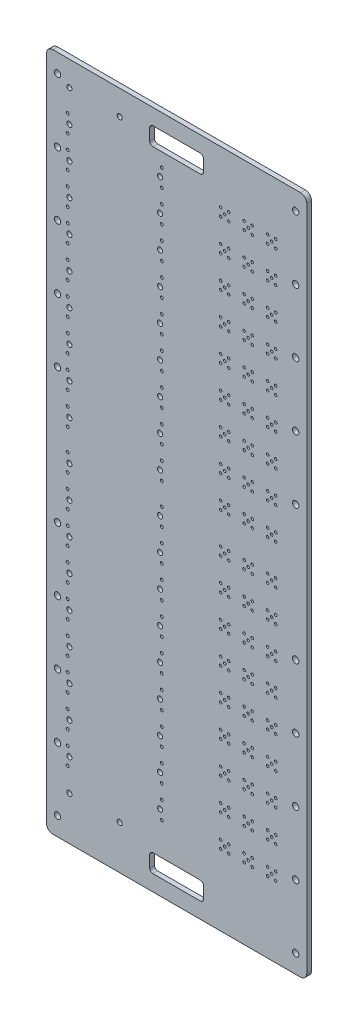
SolidWorks part; units mm, degrees
ref_plane "Front Plane" through (0, 0, 0) normal (0, 0, 1) x (1, 0, 0)
ref_plane "Top Plane" through (0, 0, 0) normal (0, 1, 0) x (1, 0, 0)
ref_plane "Right Plane" through (0, 0, 0) normal (1, 0, 0) x (0, 0, -1)
ref_plane "Plane1" through (0, 0, 0) normal (0, 0, -1) x (-1, 0, 0)
sketch "Sketch1" plane through (0, 0, 0) normal (0, 0, -1) x (-1, 0, 0)
  line L0 (7.475, 96.3) -> (-7.475, 96.3)
  line L1 (-8.475, 97.3) -> (-8.475, 101)
  line L2 (-7.475, 102) -> (7.475, 102)
  line L3 (8.475, 101) -> (8.475, 97.3)
  line L4 (39, 107) -> (-39, 107)
  line L5 (-41, 105) -> (-41, -105)
  line L6 (-39, -107) -> (39, -107)
  line L7 (41, -105) -> (41, 105)
  line L8 (-8.475, -101) -> (-8.475, -97.3)
  line L9 (-7.475, -96.3) -> (7.475, -96.3)
  line L10 (8.475, -97.3) -> (8.475, -101)
  line L11 (7.475, -102) -> (-7.475, -102)
  line L12 (-37.5, 101.2) -> (-37.5, 81.2) construction
  line L13 (-37.5, 81.2) -> (-37.5, 61.2) construction
  line L14 (-37.5, 61.2) -> (-37.5, 41.2) construction
  line L15 (-37.5, 41.2) -> (-37.5, 21.2) construction
  line L16 (37.5, 101.2) -> (37.5, 81.2) construction
  line L17 (37.5, 81.2) -> (37.5, 61.2) construction
  line L18 (37.5, 61.2) -> (37.5, 41.2) construction
  line L19 (37.5, 41.2) -> (37.5, 21.2) construction
  line L20 (37.5, -21.2) -> (37.5, -41.2) construction
  line L21 (37.5, -41.2) -> (37.5, -61.2) construction
  line L22 (37.5, -61.2) -> (37.5, -81.2) construction
  line L23 (37.5, -81.2) -> (37.5, -101.2) construction
  line L24 (-37.5, -101.2) -> (-37.5, -81.2) construction
  line L25 (-37.5, -81.2) -> (-37.5, -61.2) construction
  line L26 (-37.5, -61.2) -> (-37.5, -41.2) construction
  line L27 (-37.5, -41.2) -> (-37.5, -21.2) construction
  line L28 (33.775, 89.25) -> (5.225, 89.25) construction
  line L29 (-13.87, 87.8811) -> (-16.41, 90.4212) construction
  line L30 (-13.87, 90.4212) -> (-16.41, 87.8812) construction
  line L31 (-13.87, -4.6189) -> (-16.41, -2.0788) construction
  line L32 (-13.87, -2.0788) -> (-16.41, -4.6188) construction
  arc A0 (8.475, 97.3) -> (7.475, 96.3) centre (7.475, 97.3) cw
  arc A1 (-7.475, 96.3) -> (-8.475, 97.3) centre (-7.475, 97.3) cw
  arc A2 (-8.475, 101) -> (-7.475, 102) centre (-7.475, 101) cw
  arc A3 (7.475, 102) -> (8.475, 101) centre (7.475, 101) cw
  circle A4 centre (5.225, -3.25) radius 0.8
  circle A5 centre (34.325, -0.5) radius 0.45
  circle A6 centre (-37.5, 101.2) radius 1
  circle A7 centre (34.325, -6) radius 0.45
  circle A8 centre (34.325, 46.5) radius 0.45
  circle A9 centre (4.675, -6) radius 0.45
  circle A10 centre (5.225, 79.25) radius 0.8
  circle A11 centre (34.325, 82) radius 0.45
  circle A12 centre (33.775, 19.25) radius 0.8
  circle A13 centre (33.775, -3.25) radius 0.8
  circle A14 centre (34.325, 26.5) radius 0.45
  circle A15 centre (4.675, -0.5) radius 0.45
  circle A16 centre (5.225, -13.25) radius 0.8
  circle A17 centre (5.225, 29.25) radius 0.8
  circle A18 centre (34.325, -10.5) radius 0.45
  circle A19 centre (34.325, 36.5) radius 0.45
  circle A20 centre (4.675, 22) radius 0.45
  circle A21 centre (34.325, -16) radius 0.45
  circle A22 centre (5.225, 19.25) radius 0.8
  circle A23 centre (4.675, -16) radius 0.45
  circle A24 centre (33.775, -13.25) radius 0.8
  circle A25 centre (34.325, 76.5) radius 0.45
  circle A26 centre (5.225, 89.25) radius 0.8
  circle A27 centre (4.675, -10.5) radius 0.45
  circle A28 centre (5.225, -23.25) radius 0.8
  circle A29 centre (34.325, -20.5) radius 0.45
  circle A30 centre (4.675, 76.5) radius 0.45
  circle A31 centre (33.775, 79.25) radius 0.8
  circle A32 centre (34.325, 32) radius 0.45
  circle A33 centre (34.325, -26) radius 0.45
  circle A34 centre (4.675, 46.5) radius 0.45
  circle A35 centre (4.675, 26.5) radius 0.45
  circle A36 centre (4.675, -26) radius 0.45
  circle A37 centre (33.775, -23.25) radius 0.8
  circle A38 centre (4.675, -20.5) radius 0.45
  circle A39 centre (5.225, -33.25) radius 0.8
  circle A40 centre (34.325, -30.5) radius 0.45
  circle A41 centre (34.325, -36) radius 0.45
  circle A42 centre (34.325, 92) radius 0.45
  circle A43 centre (33.775, -93.25) radius 0.8
  circle A44 centre (4.675, 32) radius 0.45
  circle A45 centre (4.675, 16.5) radius 0.45
  circle A46 centre (4.675, -36) radius 0.45
  circle A47 centre (4.675, 82) radius 0.45
  circle A48 centre (5.225, 69.25) radius 0.8
  circle A49 centre (34.325, 16.5) radius 0.45
  circle A50 centre (33.775, -33.25) radius 0.8
  circle A51 centre (4.675, -30.5) radius 0.45
  circle A52 centre (4.675, 36.5) radius 0.45
  circle A53 centre (5.225, -43.25) radius 0.8
  circle A54 centre (34.325, 86.5) radius 0.45
  circle A55 centre (33.775, 29.25) radius 0.8
  circle A56 centre (34.325, -40.5) radius 0.45
  circle A57 centre (34.325, -46) radius 0.45
  circle A58 centre (4.675, -46) radius 0.45
  circle A59 centre (33.775, 39.25) radius 0.8
  circle A60 centre (34.325, 72) radius 0.45
  circle A61 centre (34.325, 12) radius 0.45
  arc A62 (-39, 107) -> (-41, 105) centre (-39, 105) ccw
  arc A63 (-41, -105) -> (-39, -107) centre (-39, -105) ccw
  arc A64 (39, -107) -> (41, -105) centre (39, -105) ccw
  arc A65 (41, 105) -> (39, 107) centre (39, 105) ccw
  circle A66 centre (33.775, -43.25) radius 0.8
  circle A67 centre (4.675, -40.5) radius 0.45
  circle A68 centre (34.325, 66.5) radius 0.45
  circle A69 centre (5.225, -53.25) radius 0.8
  circle A70 centre (33.775, 9.25) radius 0.8
  circle A71 centre (34.325, -50.5) radius 0.45
  circle A72 centre (34.325, -56) radius 0.45
  circle A73 centre (4.675, -56) radius 0.45
  circle A74 centre (33.775, -53.25) radius 0.8
  circle A75 centre (4.675, 66.5) radius 0.45
  circle A76 centre (4.675, -50.5) radius 0.45
  circle A77 centre (33.775, 99.25) radius 0.8
  circle A78 centre (5.225, -63.25) radius 0.8
  circle A79 centre (33.775, 69.25) radius 0.8
  circle A80 centre (-37.5, 21.2) radius 1
  circle A81 centre (4.675, 72) radius 0.45
  circle A82 centre (34.325, -60.5) radius 0.45
  circle A83 centre (5.225, 59.25) radius 0.8
  circle A84 centre (4.675, 86.5) radius 0.45
  circle A85 centre (34.325, -66) radius 0.45
  circle A86 centre (4.675, 6.5) radius 0.45
  circle A87 centre (34.325, 62) radius 0.45
  circle A88 centre (4.675, -66) radius 0.45
  circle A89 centre (33.775, -63.25) radius 0.8
  circle A90 centre (4.675, 42) radius 0.45
  circle A91 centre (4.675, -60.5) radius 0.45
  circle A92 centre (34.325, 56.5) radius 0.45
  circle A93 centre (4.675, 56.5) radius 0.45
  circle A94 centre (5.225, -73.25) radius 0.8
  circle A95 centre (33.775, 89.25) radius 0.8
  circle A96 centre (17.925, -93.25) radius 0.8
  circle A97 centre (34.325, 22) radius 0.45
  circle A98 centre (33.775, 59.25) radius 0.8
  circle A99 centre (17.925, 99.25) radius 0.8
  circle A100 centre (4.675, 12) radius 0.45
  circle A101 centre (34.325, -70.5) radius 0.45
  circle A102 centre (4.675, 62) radius 0.45
  circle A103 centre (34.325, -76) radius 0.45
  circle A104 centre (4.675, -76) radius 0.45
  circle A105 centre (5.225, 39.25) radius 0.8
  circle A106 centre (33.775, -73.25) radius 0.8
  circle A107 centre (4.675, -70.5) radius 0.45
  circle A108 centre (-21.27, -12.0789) radius 0.4
  circle A109 centre (-23.81, -12.0789) radius 0.4
  circle A110 centre (-23.81, -14.6189) radius 0.4
  circle A111 centre (-22.54, -13.3489) radius 0.4
  circle A112 centre (-21.27, -14.6189) radius 0.4
  circle A113 centre (37.5, -21.2) radius 1
  circle A114 centre (-28.67, -12.0789) radius 0.4
  circle A115 centre (-31.21, -12.0789) radius 0.4
  circle A116 centre (-31.21, -14.6189) radius 0.4
  circle A117 centre (-29.94, -13.3489) radius 0.4
  circle A118 centre (-28.67, -14.6189) radius 0.4
  circle A119 centre (-13.87, -12.0788) radius 0.4
  circle A120 centre (-16.41, -12.0788) radius 0.4
  circle A121 centre (-16.41, -14.6188) radius 0.4
  circle A122 centre (-15.14, -13.3488) radius 0.4
  circle A123 centre (-13.87, -14.6189) radius 0.4
  circle A124 centre (-21.27, -22.0789) radius 0.4
  circle A125 centre (-23.81, -22.0789) radius 0.4
  circle A126 centre (-23.81, -24.6189) radius 0.4
  circle A127 centre (-22.54, -23.3489) radius 0.4
  circle A128 centre (-21.27, -24.6189) radius 0.4
  circle A129 centre (-28.67, -22.0789) radius 0.4
  circle A130 centre (-31.21, -22.0789) radius 0.4
  circle A131 centre (-31.21, -24.6189) radius 0.4
  circle A132 centre (-29.94, -23.3489) radius 0.4
  circle A133 centre (-28.67, -24.6189) radius 0.4
  circle A134 centre (-13.87, -22.0788) radius 0.4
  circle A135 centre (-16.41, -22.0788) radius 0.4
  circle A136 centre (-16.41, -24.6188) radius 0.4
  circle A137 centre (-15.14, -23.3489) radius 0.4
  circle A138 centre (-13.87, -24.6189) radius 0.4
  circle A139 centre (-21.27, -32.0789) radius 0.4
  circle A140 centre (-23.81, -32.0789) radius 0.4
  circle A141 centre (-23.81, -34.6189) radius 0.4
  circle A142 centre (-22.54, -33.3489) radius 0.4
  circle A143 centre (-21.27, -34.6189) radius 0.4
  circle A144 centre (-28.67, -32.0789) radius 0.4
  circle A145 centre (-31.21, -32.0789) radius 0.4
  circle A146 centre (-31.21, -34.6189) radius 0.4
  circle A147 centre (-29.94, -33.3489) radius 0.4
  circle A148 centre (-28.67, -34.6189) radius 0.4
  circle A149 centre (-13.87, -32.0788) radius 0.4
  circle A150 centre (-16.41, -32.0788) radius 0.4
  circle A151 centre (-16.41, -34.6188) radius 0.4
  circle A152 centre (-15.14, -33.3488) radius 0.4
  circle A153 centre (-13.87, -34.6189) radius 0.4
  circle A154 centre (-21.27, -42.0789) radius 0.4
  circle A155 centre (-23.81, -42.0789) radius 0.4
  circle A156 centre (-23.81, -44.6189) radius 0.4
  circle A157 centre (-22.54, -43.3489) radius 0.4
  circle A158 centre (-21.27, -44.6189) radius 0.4
  circle A159 centre (-28.67, -42.0789) radius 0.4
  circle A160 centre (-31.21, -42.0789) radius 0.4
  circle A161 centre (-31.21, -44.6189) radius 0.4
  circle A162 centre (-29.94, -43.3489) radius 0.4
  circle A163 centre (-21.27, 80.4211) radius 0.4
  circle A164 centre (-23.81, 80.4211) radius 0.4
  circle A165 centre (-23.81, 77.8811) radius 0.4
  circle A166 centre (-22.54, 79.1511) radius 0.4
  circle A167 centre (-21.27, 77.8811) radius 0.4
  circle A168 centre (-28.67, 80.4211) radius 0.4
  circle A169 centre (-31.21, 80.4211) radius 0.4
  circle A170 centre (-31.21, 77.8811) radius 0.4
  circle A171 centre (-29.94, 79.1511) radius 0.4
  circle A172 centre (-28.67, 77.8811) radius 0.4
  circle A173 centre (-28.67, -44.6189) radius 0.4
  circle A174 centre (-13.87, -42.0788) radius 0.4
  circle A175 centre (-16.41, -42.0788) radius 0.4
  circle A176 centre (-16.41, -44.6188) radius 0.4
  circle A177 centre (-15.14, -43.3488) radius 0.4
  circle A178 centre (-13.87, -44.6189) radius 0.4
  circle A179 centre (-21.27, -52.0789) radius 0.4
  circle A180 centre (-23.81, -52.0789) radius 0.4
  circle A181 centre (-23.81, -54.6189) radius 0.4
  circle A182 centre (-22.54, -53.3489) radius 0.4
  circle A183 centre (-21.27, -54.6189) radius 0.4
  circle A184 centre (-28.67, -52.0789) radius 0.4
  circle A185 centre (-31.21, -52.0789) radius 0.4
  circle A186 centre (-31.21, -54.6189) radius 0.4
  circle A187 centre (-29.94, -53.3489) radius 0.4
  circle A188 centre (-13.87, 80.4212) radius 0.4
  circle A189 centre (-16.41, 80.4212) radius 0.4
  circle A190 centre (-16.41, 77.8812) radius 0.4
  circle A191 centre (-15.14, 79.1512) radius 0.4
  circle A192 centre (-13.87, 77.8811) radius 0.4
  circle A193 centre (-21.27, 70.4211) radius 0.4
  circle A194 centre (-23.81, 70.4211) radius 0.4
  circle A195 centre (-23.81, 67.8811) radius 0.4
  circle A196 centre (-22.54, 69.1511) radius 0.4
  circle A197 centre (-21.27, 67.8811) radius 0.4
  circle A198 centre (-28.67, 70.4211) radius 0.4
  circle A199 centre (-31.21, 70.4211) radius 0.4
  circle A200 centre (-31.21, 67.8811) radius 0.4
  circle A201 centre (-29.94, 69.1511) radius 0.4
  circle A202 centre (-28.67, 67.8811) radius 0.4
  circle A203 centre (-13.87, 70.4211) radius 0.4
  circle A204 centre (-16.41, 70.4211) radius 0.4
  circle A205 centre (-16.41, 67.8812) radius 0.4
  circle A206 centre (-15.14, 69.1512) radius 0.4
  circle A207 centre (-13.87, 67.8811) radius 0.4
  circle A208 centre (-21.27, 60.4211) radius 0.4
  circle A209 centre (-23.81, 60.4211) radius 0.4
  circle A210 centre (-23.81, 57.8811) radius 0.4
  circle A211 centre (-22.54, 59.1511) radius 0.4
  circle A212 centre (-21.27, 57.8811) radius 0.4
  circle A213 centre (-28.67, 60.4211) radius 0.4
  circle A214 centre (-31.21, 60.4211) radius 0.4
  circle A215 centre (-31.21, 57.8811) radius 0.4
  circle A216 centre (-29.94, 59.1511) radius 0.4
  circle A217 centre (-28.67, 57.8811) radius 0.4
  circle A218 centre (-13.87, 60.4212) radius 0.4
  circle A219 centre (-16.41, 60.4212) radius 0.4
  circle A220 centre (-16.41, 57.8812) radius 0.4
  circle A221 centre (-15.14, 59.1512) radius 0.4
  circle A222 centre (-13.87, 57.8811) radius 0.4
  circle A223 centre (-21.27, 50.4211) radius 0.4
  circle A224 centre (-23.81, 50.4211) radius 0.4
  circle A225 centre (-23.81, 47.8811) radius 0.4
  circle A226 centre (-22.54, 49.1511) radius 0.4
  circle A227 centre (-21.27, 47.8811) radius 0.4
  circle A228 centre (-28.67, -54.6189) radius 0.4
  circle A229 centre (-13.87, -52.0788) radius 0.4
  circle A230 centre (-16.41, -52.0788) radius 0.4
  circle A231 centre (-16.41, -54.6188) radius 0.4
  circle A232 centre (-15.14, -53.3489) radius 0.4
  circle A233 centre (-13.87, -54.6189) radius 0.4
  circle A234 centre (-21.27, -62.0789) radius 0.4
  circle A235 centre (-23.81, -62.0789) radius 0.4
  circle A236 centre (-23.81, -64.6189) radius 0.4
  circle A237 centre (-22.54, -63.3489) radius 0.4
  circle A238 centre (-21.27, -64.6189) radius 0.4
  circle A239 centre (-28.67, -62.0789) radius 0.4
  circle A240 centre (-31.21, -62.0789) radius 0.4
  circle A241 centre (-31.21, -64.6189) radius 0.4
  circle A242 centre (-29.94, -63.3489) radius 0.4
  circle A243 centre (-28.67, 50.4211) radius 0.4
  circle A244 centre (-31.21, 50.4211) radius 0.4
  circle A245 centre (-31.21, 47.8811) radius 0.4
  circle A246 centre (-29.94, 49.1511) radius 0.4
  circle A247 centre (-28.67, 47.8811) radius 0.4
  circle A248 centre (-13.87, 50.4212) radius 0.4
  circle A249 centre (-16.41, 50.4212) radius 0.4
  circle A250 centre (-16.41, 47.8812) radius 0.4
  circle A251 centre (-15.14, 49.1511) radius 0.4
  circle A252 centre (-13.87, 47.8811) radius 0.4
  circle A253 centre (-21.27, 40.4211) radius 0.4
  circle A254 centre (-23.81, 40.4211) radius 0.4
  circle A255 centre (-23.81, 37.8811) radius 0.4
  circle A256 centre (-22.54, 39.1511) radius 0.4
  circle A257 centre (-21.27, 37.8811) radius 0.4
  circle A258 centre (-28.67, 40.4211) radius 0.4
  circle A259 centre (-31.21, 40.4211) radius 0.4
  circle A260 centre (-31.21, 37.8811) radius 0.4
  circle A261 centre (-29.94, 39.1511) radius 0.4
  circle A262 centre (-28.67, 37.8811) radius 0.4
  circle A263 centre (-13.87, 40.4212) radius 0.4
  circle A264 centre (-16.41, 40.4212) radius 0.4
  circle A265 centre (-16.41, 37.8812) radius 0.4
  circle A266 centre (-15.14, 39.1511) radius 0.4
  circle A267 centre (-13.87, 37.8811) radius 0.4
  circle A268 centre (-21.27, 30.4211) radius 0.4
  circle A269 centre (-23.81, 30.4211) radius 0.4
  circle A270 centre (-23.81, 27.8811) radius 0.4
  circle A271 centre (-22.54, 29.1511) radius 0.4
  circle A272 centre (-21.27, 27.8811) radius 0.4
  circle A273 centre (-28.67, 30.4211) radius 0.4
  circle A274 centre (-31.21, 30.4211) radius 0.4
  circle A275 centre (-31.21, 27.8811) radius 0.4
  circle A276 centre (-29.94, 29.1511) radius 0.4
  circle A277 centre (-28.67, 27.8811) radius 0.4
  circle A278 centre (-13.87, 30.4212) radius 0.4
  circle A279 centre (-16.41, 30.4212) radius 0.4
  circle A280 centre (-16.41, 27.8812) radius 0.4
  circle A281 centre (-15.14, 29.1512) radius 0.4
  circle A282 centre (-13.87, 27.8811) radius 0.4
  circle A283 centre (-28.67, -64.6189) radius 0.4
  circle A284 centre (-13.87, -62.0788) radius 0.4
  circle A285 centre (-16.41, -62.0788) radius 0.4
  circle A286 centre (-16.41, -64.6188) radius 0.4
  circle A287 centre (-15.14, -63.3488) radius 0.4
  circle A288 centre (-13.87, -64.6189) radius 0.4
  circle A289 centre (-21.27, -72.0789) radius 0.4
  circle A290 centre (-23.81, -72.0789) radius 0.4
  circle A291 centre (-23.81, -74.6189) radius 0.4
  circle A292 centre (-22.54, -73.3489) radius 0.4
  circle A293 centre (-21.27, -74.6189) radius 0.4
  circle A294 centre (-28.67, -72.0789) radius 0.4
  circle A295 centre (-31.21, -72.0789) radius 0.4
  circle A296 centre (-31.21, -74.6189) radius 0.4
  circle A297 centre (-29.94, -73.3489) radius 0.4
  circle A298 centre (-21.27, 20.4211) radius 0.4
  circle A299 centre (-23.81, 20.4211) radius 0.4
  circle A300 centre (-23.81, 17.8811) radius 0.4
  circle A301 centre (-22.54, 19.1511) radius 0.4
  circle A302 centre (-21.27, 17.8811) radius 0.4
  circle A303 centre (-28.67, 20.4211) radius 0.4
  circle A304 centre (-31.21, 20.4211) radius 0.4
  circle A305 centre (-31.21, 17.8811) radius 0.4
  circle A306 centre (-29.94, 19.1511) radius 0.4
  circle A307 centre (-28.67, 17.8811) radius 0.4
  circle A308 centre (-13.87, 20.4211) radius 0.4
  circle A309 centre (-16.41, 20.4211) radius 0.4
  circle A310 centre (-16.41, 17.8811) radius 0.4
  circle A311 centre (-15.14, 19.1511) radius 0.4
  circle A312 centre (-13.87, 17.8811) radius 0.4
  circle A313 centre (-21.27, 10.4211) radius 0.4
  circle A314 centre (-23.81, 10.4211) radius 0.4
  circle A315 centre (-23.81, 7.8811) radius 0.4
  circle A316 centre (-22.54, 9.1511) radius 0.4
  circle A317 centre (-21.27, 7.8811) radius 0.4
  circle A318 centre (-28.67, 10.4211) radius 0.4
  circle A319 centre (-31.21, 10.4211) radius 0.4
  circle A320 centre (-31.21, 7.8811) radius 0.4
  circle A321 centre (-29.94, 9.1511) radius 0.4
  circle A322 centre (-28.67, 7.8811) radius 0.4
  circle A323 centre (-13.87, 10.4212) radius 0.4
  circle A324 centre (-16.41, 10.4212) radius 0.4
  circle A325 centre (-16.41, 7.8812) radius 0.4
  circle A326 centre (-15.14, 9.1511) radius 0.4
  circle A327 centre (-13.87, 7.8811) radius 0.4
  circle A328 centre (-21.27, 90.4211) radius 0.4
  circle A329 centre (-23.81, 90.4211) radius 0.4
  circle A330 centre (-23.81, 87.8811) radius 0.4
  circle A331 centre (-22.54, 89.1511) radius 0.4
  circle A332 centre (-21.27, 87.8811) radius 0.4
  circle A333 centre (-28.67, 90.4211) radius 0.4
  circle A334 centre (-31.21, 90.4211) radius 0.4
  circle A335 centre (-31.21, 87.8811) radius 0.4
  circle A336 centre (-29.94, 89.1511) radius 0.4
  circle A337 centre (-28.67, 87.8811) radius 0.4
  circle A338 centre (-28.67, -74.6189) radius 0.4
  circle A339 centre (-13.87, -72.0789) radius 0.4
  circle A340 centre (-16.41, -72.0789) radius 0.4
  circle A341 centre (-16.41, -74.6188) radius 0.4
  circle A342 centre (-15.14, -73.3489) radius 0.4
  circle A343 centre (-13.87, -74.6189) radius 0.4
  circle A344 centre (-21.27, -82.0789) radius 0.4
  circle A345 centre (-23.81, -82.0789) radius 0.4
  circle A346 centre (-23.81, -84.6189) radius 0.4
  circle A347 centre (-22.54, -83.3489) radius 0.4
  circle A348 centre (-21.27, -84.6189) radius 0.4
  circle A349 centre (-28.67, -82.0789) radius 0.4
  circle A350 centre (-31.21, -82.0789) radius 0.4
  circle A351 centre (-31.21, -84.6189) radius 0.4
  circle A352 centre (-29.94, -83.3489) radius 0.4
  circle A353 centre (-13.87, 90.4212) radius 0.4
  circle A354 centre (-16.41, 90.4212) radius 0.4
  circle A355 centre (-16.41, 87.8812) radius 0.4
  circle A356 centre (-15.14, 89.1512) radius 0.4
  circle A357 centre (-13.87, 87.8811) radius 0.4
  circle A358 centre (5.225, -83.25) radius 0.8
  circle A359 centre (34.325, -80.5) radius 0.45
  circle A360 centre (34.325, 6.5) radius 0.45
  circle A361 centre (4.675, 92) radius 0.45
  circle A362 centre (5.225, 49.25) radius 0.8
  circle A363 centre (34.325, -86) radius 0.45
  circle A364 centre (4.675, -86) radius 0.45
  circle A365 centre (34.325, 42) radius 0.45
  circle A366 centre (34.325, 52) radius 0.45
  circle A367 centre (34.325, 46.5) radius 0.45
  circle A368 centre (33.775, -83.25) radius 0.8
  circle A369 centre (5.225, 9.25) radius 0.8
  circle A370 centre (4.675, 46.5) radius 0.45
  circle A371 centre (4.675, -80.5) radius 0.45
  circle A372 centre (-28.67, -84.6189) radius 0.4
  circle A373 centre (-13.87, -82.0788) radius 0.4
  circle A374 centre (-16.41, -82.0788) radius 0.4
  circle A375 centre (-16.41, -84.6188) radius 0.4
  circle A376 centre (-15.14, -83.3488) radius 0.4
  circle A377 centre (-13.87, -84.6189) radius 0.4
  circle A378 centre (-21.27, -2.0789) radius 0.4
  circle A379 centre (-23.81, -2.0789) radius 0.4
  circle A380 centre (-23.81, -4.6189) radius 0.4
  circle A381 centre (-22.54, -3.3489) radius 0.4
  circle A382 centre (-21.27, -4.6189) radius 0.4
  circle A383 centre (-28.67, -2.0789) radius 0.4
  circle A384 centre (-31.21, -2.0789) radius 0.4
  circle A385 centre (-31.21, -4.6189) radius 0.4
  circle A386 centre (-29.94, -3.3489) radius 0.4
  circle A387 centre (-28.67, -4.6189) radius 0.4
  circle A388 centre (-13.87, -2.0788) radius 0.4
  circle A389 centre (-16.41, -2.0788) radius 0.4
  circle A390 centre (-16.41, -4.6188) radius 0.4
  circle A391 centre (-15.14, -3.3489) radius 0.4
  circle A392 centre (-13.87, -4.6189) radius 0.4
  circle A408 centre (-37.5, -81.2) radius 1
  circle A409 centre (37.5, 61.2) radius 1
  circle A410 centre (37.5, -101.2) radius 1
  circle A411 centre (37.5, -61.2) radius 1
  circle A412 centre (-37.5, 81.2) radius 1
  circle A413 centre (-37.5, -41.2) radius 1
  circle A414 centre (-37.5, -101.2) radius 1
  circle A415 centre (-37.5, 61.2) radius 1
  circle A416 centre (37.5, 21.2) radius 1
  circle A417 centre (-37.5, 41.2) radius 1
  circle A418 centre (37.5, -41.2) radius 1
  circle A419 centre (37.5, -81.2) radius 1
  circle A420 centre (-37.5, -61.2) radius 1
  circle A421 centre (37.5, 81.2) radius 1
  circle A422 centre (-37.5, -21.2) radius 1
  circle A423 centre (37.5, 101.2) radius 1
  circle A424 centre (37.5, 41.2) radius 1
  arc A425 (-8.475, -97.3) -> (-7.475, -96.3) centre (-7.475, -97.3) cw
  arc A426 (7.475, -96.3) -> (8.475, -97.3) centre (7.475, -97.3) cw
  arc A427 (8.475, -101) -> (7.475, -102) centre (7.475, -101) cw
  arc A428 (-7.475, -102) -> (-8.475, -101) centre (-7.475, -101) cw
  circle A429 centre (33.775, 49.25) radius 0.8
  circle A430 centre (4.675, 52) radius 0.45
  circle A431 centre (5.225, 39.25) radius 0.8
  circle A432 centre (34.325, 42) radius 0.45
  circle A433 centre (34.325, 36.5) radius 0.45
  circle A434 centre (4.675, 36.5) radius 0.45
  circle A435 centre (33.775, 39.25) radius 0.8
  circle A436 centre (4.675, 42) radius 0.45
  circle A437 centre (5.225, 29.25) radius 0.8
  circle A438 centre (34.325, 32) radius 0.45
  circle A439 centre (34.325, 26.5) radius 0.45
  circle A440 centre (4.675, 26.5) radius 0.45
  circle A441 centre (33.775, 29.25) radius 0.8
  circle A442 centre (4.675, 32) radius 0.45
  circle A443 centre (5.225, 19.25) radius 0.8
  circle A444 centre (34.325, 22) radius 0.45
  circle A445 centre (34.325, 16.5) radius 0.45
  circle A446 centre (4.675, 16.5) radius 0.45
  circle A447 centre (33.775, 19.25) radius 0.8
  circle A448 centre (4.675, 22) radius 0.45
  circle A449 centre (5.225, 9.25) radius 0.8
  circle A450 centre (34.325, 12) radius 0.45
  circle A451 centre (34.325, 6.5) radius 0.45
  circle A452 centre (4.675, 6.5) radius 0.45
  circle A453 centre (33.775, 9.25) radius 0.8
  circle A454 centre (4.675, 12) radius 0.45
  dimension "D2" = 1.6
  dimension "D3" = 2
  dimension "D8" = 2
  dimension "D18" = 1.6
  dimension "D21" = 0.9
  dimension "D35" = 1
  dimension "D40" = 0.8
  dimension "D41" = 0.8
  dimension "D1" = 15.85
  dimension "D4" = 7.75
  dimension "D5" = 7.225
  dimension "D6" = 214
  dimension "D7" = 82
  dimension "D9" = 41
  dimension "D10" = 107
  dimension "D11" = 3.5
  dimension "D12" = 5.8
  dimension "D13" = 75
  dimension "D14" = 42.4
  dimension "D15" = 20
  dimension "D16" = 7.225
  dimension "D17" = 17.75
  dimension "D19" = 0.55
  dimension "D20" = 2.75
  dimension "D22" = 28.55
  dimension "D23" = 29.65
  dimension "D25" = 10
  dimension "D27" = 92.5
  dimension "D29" = 10
  dimension "D30" = 13.75
  dimension "D31" = 7.225
  dimension "D32" = 15.85
  dimension "D33" = 16.95
  dimension "D34" = 5.7
  dimension "D36" = 32.525
  dimension "D37" = 5
  dimension "D38" = 5
  dimension "D39" = 5.7
  dimension "D42" = 1.27
  dimension "D43" = 1.27
  dimension "D44" = 17.8489
  dimension "D45" = 25.86
  dimension "D46" = 1.27
  dimension "D48" = 7.4
  dimension "D50" = 10
  dimension "D52" = 92.5
  dimension "D24" = 9
  dimension "D26" = 2
  dimension "D28" = 9
  dimension "D47" = 3
  dimension "D49" = 9
  dimension "D51" = 2
extrude "Boss-Extrude1" add sketch "Sketch1" against normal blind 1.5
